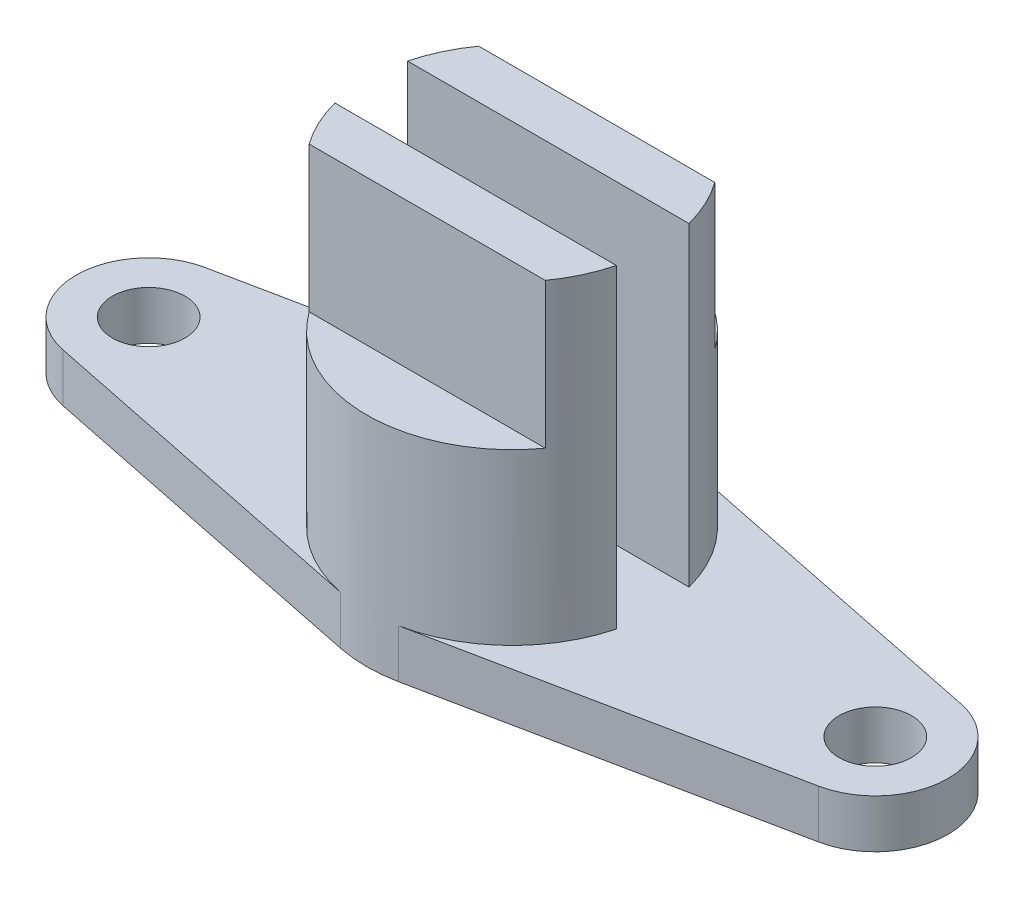
SolidWorks part; units mm, degrees
ref_plane "Front Plane" through (0, 0, 0) normal (0, 0, 1) x (1, 0, 0)
ref_plane "Top Plane" through (0, 0, 0) normal (0, 1, 0) x (1, 0, 0)
ref_plane "Right Plane" through (0, 0, 0) normal (1, 0, 0) x (0, 0, -1)
sketch "Sketch1" plane through (0, 0, 0) normal (0, 1, 0) x (1, 0, 0)
  line L0 (6, 29.3939) -> (78, 14.6969)
  line L1 (6, -29.3939) -> (78, -14.6969)
  line L2 (0, 69.3548) -> (0, -47.5806) construction
  line L3 (-6, -29.3939) -> (-78, -14.6969)
  line L4 (-6, 29.3939) -> (-78, 14.6969)
  arc A0 (78, 14.6969) -> (78, -14.6969) centre (75, 0) cw
  arc A1 (-78, 14.6969) -> (-78, -14.6969) centre (-75, 0) ccw
  circle A2 centre (-75, 0) radius 7.5
  circle A3 centre (75, 0) radius 7.5
  arc A4 (-6, -29.3939) -> (6, -29.3939) centre (0, 0) ccw
  arc A5 (6, 29.3939) -> (-6, 29.3939) centre (0, 0) ccw
  dimension "D2" = 15
  dimension "D3" = 15
  dimension "D4" = 60
  dimension "D1" = 150
extrude "Boss-Extrude1" add sketch "Sketch1" along normal blind 10
sketch "Sketch2" plane through (0, 10, 0) normal (0, 1, 0) x (1, 0, 0)
  circle A0 centre (0, 0) radius 30
  dimension "D1" = 60
extrude "Boss-Extrude2" add sketch "Sketch2" along normal blind 65
sketch "Sketch3" plane through (0, 0, 0) normal (1, 0, 0) x (0, 0, -1)
  line L0 (30, 75) -> (-30, 75) construction
  line L1 (7.5, 75) -> (-7.5, 75)
  line L2 (-7.5, 75) -> (-7.5, 10)
  line L4 (7.5, 75) -> (7.5, 10)
  line L5 (29.3939, 10) -> (-29.3939, 10) construction
  line L6 (7.5, 10) -> (-7.5, 10)
  line L7 (30, 0) -> (30, 75) construction
  point P3 (-88.3011, 58.5169)
  point P4 (-173.5234, 105.009)
  dimension "D1" = 15
  dimension "D2" = 22.5
extrude "Cut-Extrude1" cut sketch "Sketch3" against normal through all and the other way through all
sketch "Sketch5" plane through (0, 0, 0) normal (1, 0, 0) x (0, 0, -1)
  line L1 (-30, 75) -> (-17.5, 75)
  line L2 (-30, 75) -> (-30, 45)
  line L3 (-30, 45) -> (-17.5, 45)
  line L4 (-17.5, 75) -> (-17.5, 45)
  dimension "D1" = 30
  dimension "D2" = 12.5
extrude "Cut-Extrude2" cut sketch "Sketch5" against normal through all both and the other way through all
mirror "Mirror1" about plane through (0, 0, 0) normal (0, 0, 1) of "Cut-Extrude2"
